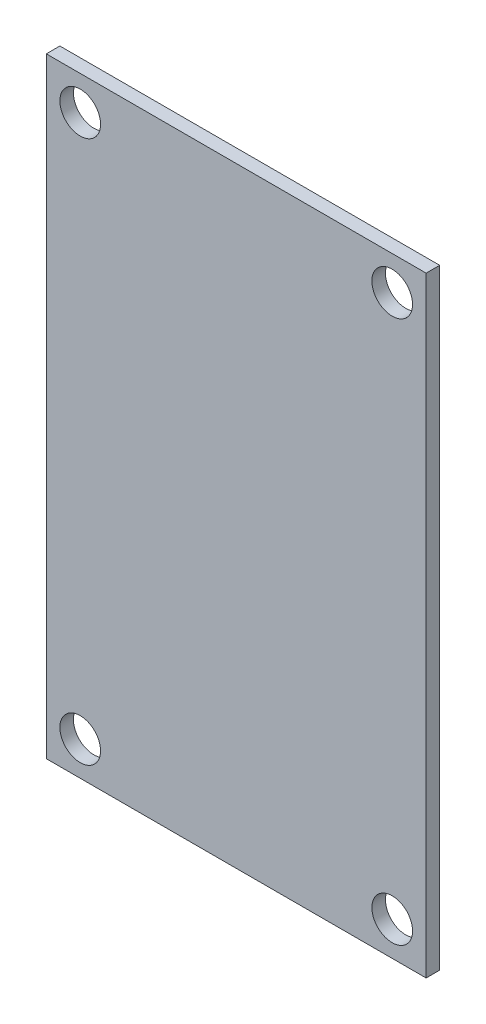
SolidWorks part; units mm, degrees
ref_plane "Alzado" through (0, 0, 0) normal (0, 0, 1) x (1, 0, 0)
ref_plane "Planta" through (0, 0, 0) normal (0, 1, 0) x (1, 0, 0)
ref_plane "Vista lateral" through (0, 0, 0) normal (1, 0, 0) x (0, 0, -1)
sketch "Croquis1" plane through (0, 0, 0) normal (0, 0, 1) x (1, 0, 0)
  line L1 (0, 0) -> (28, 0)
  line L2 (0, 0) -> (0, -45)
  line L3 (0, -45) -> (28, -45)
  line L4 (28, 0) -> (28, -45)
  dimension "D1" = 28
  dimension "D2" = 45
extrude "Saliente-Extruir1" add sketch "Croquis1" along normal blind 1
sketch "Croquis2" plane through (0, 0, 1) normal (0, 0, 1) x (1, 0, 0)
  line L0 (0, -45) -> (2.5, -45) construction
  line L1 (0, -45) -> (28, -45) construction
  line L3 (0, 0) -> (0, -45) construction
  line L4 (0, -22.5) -> (28, -22.5) construction
  line L5 (28, -45) -> (28, 0) construction
  line L6 (14, 0) -> (14, -45) construction
  line L7 (28, 0) -> (0, 0) construction
  circle A0 centre (2.5, -42.5) radius 1.5
  circle A1 centre (2.5, -2.5) radius 1.5
  circle A2 centre (25.5, -42.5) radius 1.5
  circle A3 centre (25.5, -2.5) radius 1.5
  dimension "D1" = 3
  dimension "D2" = 2.5
  dimension "D3" = 2.5
extrude "Cortar-Extruir1" cut sketch "Croquis2" against normal through all
